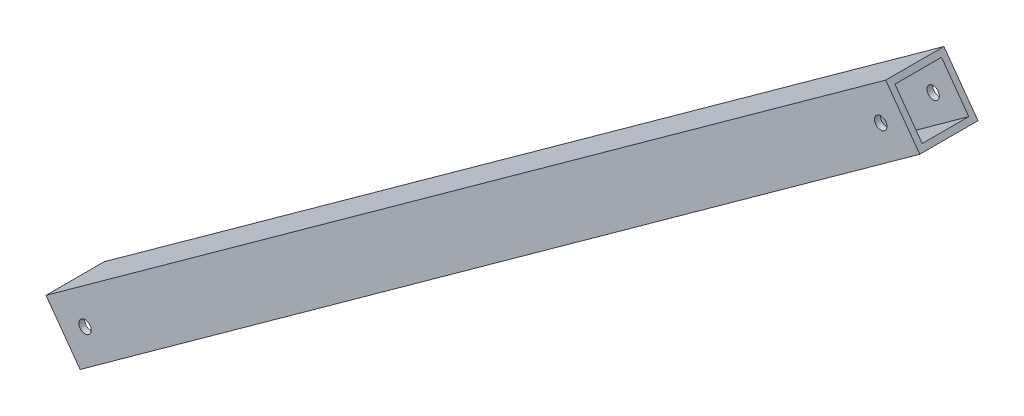
SolidWorks part; units mm, degrees
ref_plane "正面" through (0, 0, 0) normal (0, 0, 1) x (1, 0, 0)
ref_plane "平面" through (0, 0, 0) normal (0, 1, 0) x (1, 0, 0)
ref_plane "右側面" through (0, 0, 0) normal (1, 0, 0) x (0, 0, -1)
sketch "ｽｹｯﾁ2" plane through (0, 0, 0) normal (0, 0, 1) x (1, 0, 0)
  line L0 (0, 0) -> (0, 148) construction
  line L1 (0, 148) -> (205, 148) construction
  line L2 (0, 0) -> (205, 148) construction
  line L3 (-10.0656, 1.9835) -> (-1.2854, -10.1783)
  line L4 (-10.0656, 1.9835) -> (206.2854, 158.1783)
  line L5 (-1.2854, -10.1783) -> (215.0656, 146.0165)
  line L6 (206.2854, 158.1783) -> (215.0656, 146.0165)
  line L7 (4.3901, -6.0809) -> (-4.3901, 6.0809) construction
  line L8 (209.3901, 141.9191) -> (200.6099, 154.0809) construction
  circle A0 centre (0, 0) radius 1.6
  circle A1 centre (205, 148) radius 1.6
  point P9 (0, 0)
  point P16 (205, 148)
  dimension "D7" = 3.2
  dimension "D1" = 205
  dimension "D2" = 148
  dimension "D3" = 15
  dimension "D4" = 7
  dimension "D5" = 7
  dimension "D6" = 266.8418
extrude "ﾎﾞｽ - 押し出し1" add sketch "ｽｹｯﾁ2" along normal blind 15
sketch "ｽｹｯﾁ3" plane through (210.6755, 152.0974, 0) normal (0.8108, 0.5853, 0) x (0, 0, -1)
  line L8 (-1.5, -6) -> (-1.5, 6)
  line L9 (-1.5, 6) -> (-13.5, 6)
  line L10 (-13.5, 6) -> (-13.5, -6)
  line L11 (-13.5, -6) -> (-1.5, -6)
  line L12 (-1.5, -6) -> (-1.5, 6)
  line L13 (-1.5, 6) -> (-13.5, 6)
  line L14 (-13.5, 6) -> (-13.5, -6)
  line L15 (-13.5, -6) -> (-1.5, -6)
  dimension "D1" = 1.5
extrude "ｶｯﾄ - 押し出し1" cut sketch "ｽｹｯﾁ3" against normal through all
